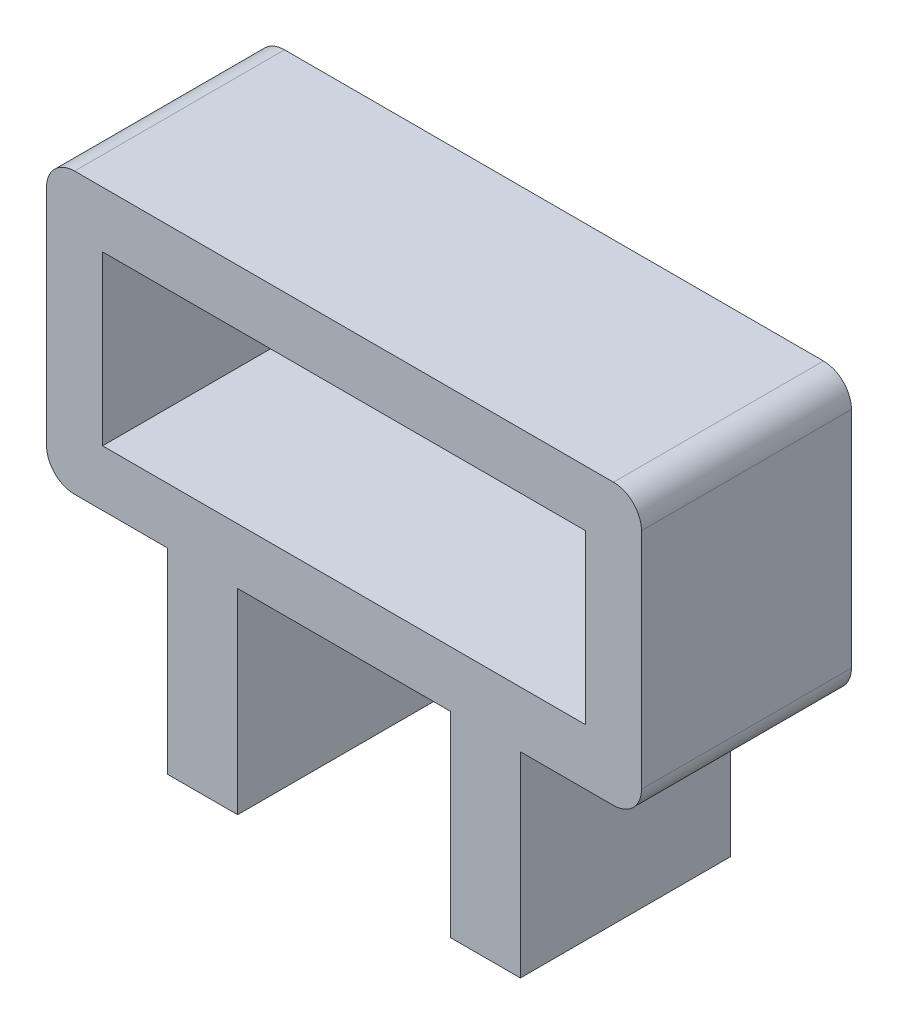
SolidWorks part; units mm, degrees
ref_plane "Front Plane" through (0, 0, 0) normal (0, 0, 1) x (1, 0, 0)
ref_plane "Top Plane" through (0, 0, 0) normal (0, 1, 0) x (1, 0, 0)
ref_plane "Right Plane" through (0, 0, 0) normal (1, 0, 0) x (0, 0, -1)
sketch "Sketch1" plane through (0, 0, 0) normal (0, 0, 1) x (1, 0, 0)
  line L0 (-19.5547, 0.0558) -> (-19.5547, -13.563) construction
  line L1 (-36.8047, 16.437) -> (-2.3047, 16.437)
  line L2 (-36.8047, 16.437) -> (-36.8047, 4.437)
  line L3 (-36.8047, 4.437) -> (-2.3047, 4.437)
  line L4 (-2.3047, 16.437) -> (-2.3047, 4.437)
  line L5 (-36.8047, 16.437) -> (-2.3047, 4.437) construction
  line L6 (-36.8047, 4.437) -> (-2.3047, 16.437) construction
  line L7 (-40.8047, 20.437) -> (1.6953, 20.437)
  line L8 (-40.8047, 20.437) -> (-40.8047, 0.437)
  line L9 (-40.8047, 0.437) -> (-32.1547, 0.437)
  line L10 (1.6953, 20.437) -> (1.6953, 0.437)
  line L11 (-40.8047, 20.437) -> (1.6953, 0.437) construction
  line L12 (-40.8047, 0.437) -> (1.6953, 20.437) construction
  line L13 (-19.5547, -13.563) -> (-11.9547, -13.563) construction
  line L14 (-11.9547, -13.563) -> (-42.0847, -13.563) construction
  line L15 (-27.1547, 0.437) -> (-27.1547, -27.3913) construction
  line L16 (-11.9547, 0.437) -> (-11.9547, -28.0241) construction
  line L17 (-27.1547, 0.437) -> (-27.1547, -13.563)
  line L18 (-27.1547, -13.563) -> (-32.1547, -13.563)
  line L19 (-32.1547, -13.563) -> (-32.1547, 0.437)
  line L20 (-11.9547, 0.437) -> (-11.9547, -13.563)
  line L22 (-6.9547, -13.563) -> (-6.9547, 0.437)
  line L23 (-27.1547, 0.437) -> (-11.9547, 0.437)
  line L24 (-6.9547, 0.437) -> (1.6953, 0.437)
  line L25 (-11.9547, -13.563) -> (-6.9547, -13.563)
  point P0 (-19.5547, 10.437)
  point P6 (-19.5547, 10.437)
  point P18 (-12.1931, -14.5731)
  point P22 (0, 0)
  point P26 (0, 0)
  point P27 (-12.046, -14.563)
  dimension "D1" = 7.6
  dimension "D2" = 7.6
  dimension "D3" = 12
  dimension "D4" = 34.5
  dimension "D5" = 14
  dimension "D6" = 5
  dimension "D7" = 5
extrude "Boss-Extrude1" add sketch "Sketch1" along normal blind 15
fillet "Fillet1" radius 2 4 edges at (-40.8047, 0.437, 7.5) (1.6953, 0.437, 7.5) (-40.8047, 20.437, 7.5) (1.6953, 20.437, 7.5)
